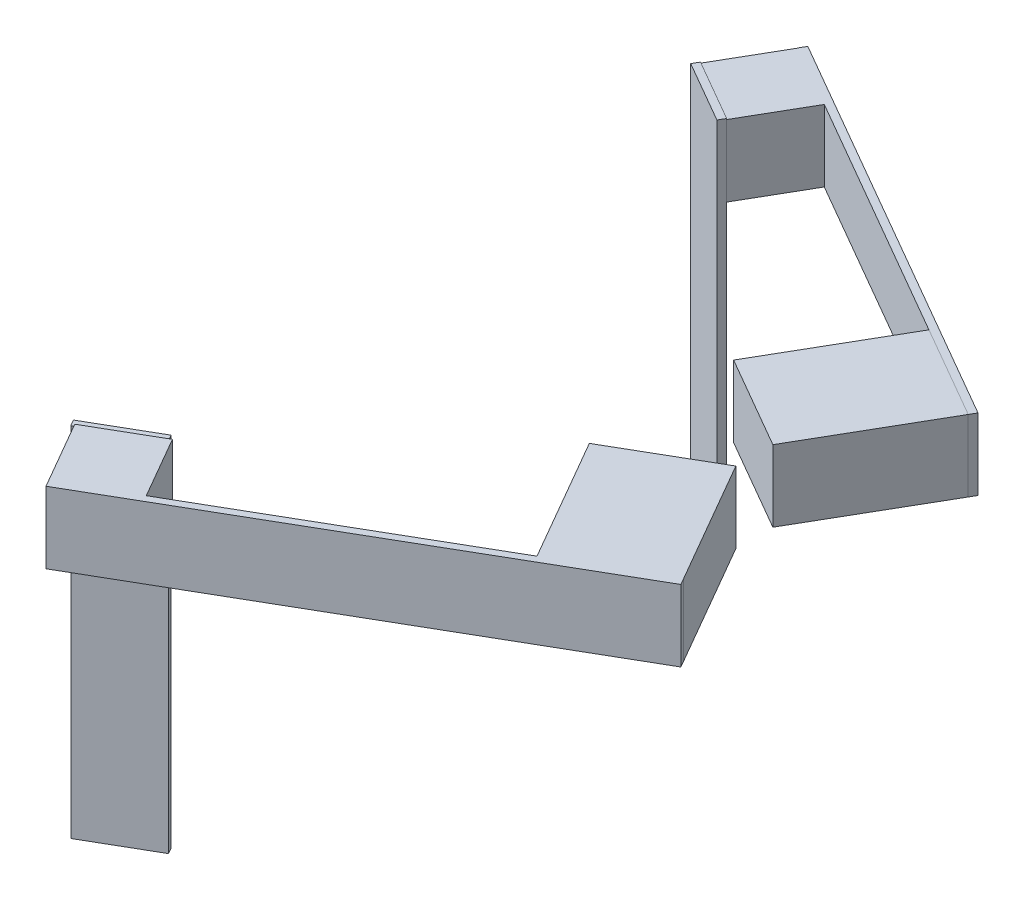
SolidWorks part; units mm, degrees
ref_plane "前视基准面" through (0, 0, 0) normal (0, 0, 1) x (1, 0, 0)
ref_plane "上视基准面" through (0, 0, 0) normal (0, 1, 0) x (1, 0, 0)
ref_plane "右视基准面" through (0, 0, 0) normal (1, 0, 0) x (0, 0, -1)
sketch "草图3" plane through (0, 0, 0) normal (0, 1, 0) x (1, 0, 0)
  line L0 (-48.9702, -5.1789) -> (-74.951, -20.1789)
  line L1 (-48.9702, -5.1789) -> (-28.9702, -39.82)
  line L2 (-74.951, -20.1789) -> (-54.951, -54.82)
  line L3 (-28.9702, -39.82) -> (-54.951, -54.82)
  line L4 (-48.9702, 5.1789) -> (-74.951, 20.1789)
  line L5 (-48.9702, 5.1789) -> (-28.9702, 39.82)
  line L6 (-74.951, 20.1789) -> (-54.951, 54.82)
  line L7 (-28.9702, 39.82) -> (-54.951, 54.82)
  point P0 (0, 0)
  dimension "D1" = 15
  dimension "D2" = 34.641
  dimension "D3" = 40
  dimension "D4" = 40
  dimension "D5" = 25.9808
  dimension "D6" = 30
extrude "凸台-拉伸1" add sketch "草图3" along normal blind 20
sketch "草图4" plane through (0, 0, 0) normal (0, 1, 0) x (1, 0, 0)
  line L0 (-28.9702, -39.82) -> (-141.5565, -104.8148)
  line L1 (-28.9702, -39.82) -> (-27.9726, -41.548)
  line L2 (-141.5565, -104.8148) -> (-140.5589, -106.5428)
  line L3 (-27.9726, -41.548) -> (-140.5589, -106.5428)
  line L4 (-28.9702, 39.82) -> (-141.5611, 104.8069)
  line L5 (-28.9702, 39.82) -> (-27.9704, 41.5521)
  line L6 (-141.5611, 104.8069) -> (-140.5613, 106.539)
  line L7 (-27.9704, 41.5521) -> (-140.5613, 106.539)
  dimension "D1" = 130
  dimension "D2" = 130
  dimension "D3" = 2
extrude "凸台-拉伸2" add sketch "草图4" along normal blind 20
ref_plane "基准面2" through (10.0002, 0, 17.3228) normal (-0.5, 0, -0.866) x (-0.866, 0, 0.5)
sketch "草图5" plane through (10.0002, 0, 17.3228) normal (-0.5, 0, -0.866) x (-0.866, 0, 0.5)
  line L0 (174.998, 20) -> (174.998, 0) construction
  line L1 (154.998, 20) -> (174.998, 20)
  line L2 (154.998, 20) -> (154.998, 0)
  line L3 (154.998, 0) -> (174.998, 0)
  line L4 (174.998, 20) -> (174.998, 0)
  line L5 (74.998, 0) -> (174.998, 0) construction
  dimension "D1" = 20
  dimension "D2" = 20
extrude "凸台-拉伸3" add sketch "草图5" along normal blind 20
ref_plane "基准面3" through (10.0006, 0, -17.3262) normal (-0.4999, 0, 0.8661) x (0.8661, 0, 0.4999)
sketch "草图6" plane through (10.0006, 0, -17.3262) normal (-0.4999, 0, 0.8661) x (0.8661, 0, 0.4999)
  line L0 (-174.9966, 0) -> (-44.9966, 0) construction
  line L1 (-174.9425, 20) -> (-154.9425, 20)
  line L2 (-174.9425, 20) -> (-174.9425, 0)
  line L3 (-174.9425, 0) -> (-154.9425, 0)
  line L4 (-154.9425, 20) -> (-154.9425, 0)
  dimension "D1" = 20
  dimension "D2" = 20
extrude "凸台-拉伸4" add sketch "草图6" along normal blind 20
ref_plane "基准面4" through (0.001, 0, 0.0018) normal (-0.5, 0, -0.866) x (-0.866, 0, 0.5)
sketch "草图7" plane through (0.001, 0, 0.0018) normal (-0.5, 0, -0.866) x (-0.866, 0, 0.5)
  line L1 (155.8117, 19.4937) -> (175.8117, 19.4937)
  line L2 (155.8117, 19.4937) -> (155.8117, -80.5063)
  line L3 (155.8117, -80.5063) -> (175.8117, -80.5063)
  line L4 (175.8117, 19.4937) -> (175.8117, -80.5063)
  dimension "D1" = 100
  dimension "D2" = 20
extrude "凸台-拉伸5" add sketch "草图7" along normal blind 2
ref_plane "基准面5" through (0.0026, 0, -0.0045) normal (-0.4999, 0, 0.8661) x (0.8661, 0, 0.4999)
sketch "草图8" plane through (0.0026, 0, -0.0045) normal (-0.4999, 0, 0.8661) x (0.8661, 0, 0.4999)
  line L1 (-174.9001, 20.2893) -> (-154.9001, 20.2893)
  line L2 (-174.9001, 20.2893) -> (-174.9001, -79.7107)
  line L3 (-174.9001, -79.7107) -> (-154.9001, -79.7107)
  line L4 (-154.9001, 20.2893) -> (-154.9001, -79.7107)
  dimension "D1" = 20
  dimension "D2" = 100
extrude "凸台-拉伸6" add sketch "草图8" along normal blind 2
